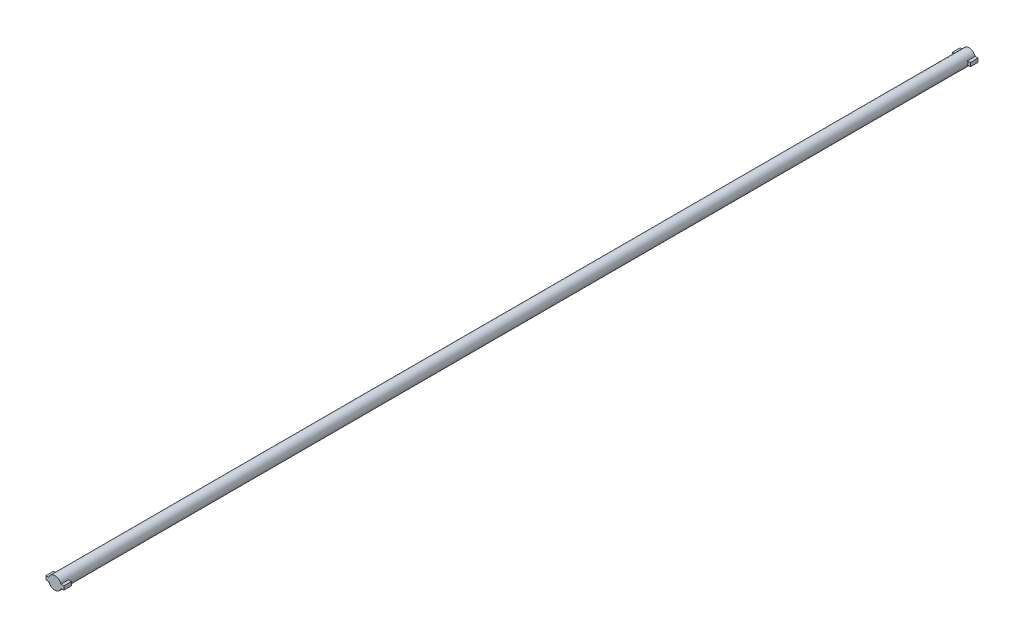
SolidWorks part; units mm, degrees
material "AISI 1020 Steel, Cold Rolled"
ref_plane "Front Plane" through (0, 0, 0) normal (0, 0, 1) x (1, 0, 0)
ref_plane "Top Plane" through (0, 0, 0) normal (0, 1, 0) x (1, 0, 0)
ref_plane "Right Plane" through (0, 0, 0) normal (1, 0, 0) x (0, 0, -1)
sketch "Sketch1" plane through (0, 0, 0) normal (0, 0, 1) x (1, 0, 0)
  circle A0 centre (0, 0) radius 3.175
  dimension "D1" = 6.35
extrude "Boss-Extrude1" add sketch "Sketch1" along normal blind 457.2
sketch "Sketch3" plane through (0, 0, 457.2) normal (0, 0, 1) x (1, 0, 0)
  line L0 (3.175, 0) -> (4.445, 0) construction
  line L1 (4.445, 0.9525) -> (4.445, -0.9525)
  line L2 (4.445, 0.9525) -> (3.0288, 0.9525)
  line L3 (4.445, -0.9525) -> (3.0288, -0.9525)
  circle A0 centre (0, 0) radius 3.175 construction
  arc A1 (3.0288, -0.9525) -> (3.0288, 0.9525) centre (0, 0) ccw
  dimension "D1" = 1.905
  dimension "D2" = 1.27
extrude "Boss-Extrude2" add sketch "Sketch3" against normal blind 3.81
pattern_circular "CirPattern1" count 2 over 360 about axis through (0, 0, 0) along (0, 0, 1) of "Boss-Extrude2"
pattern_linear "LPattern1" count 2 spacing 453.39 along (0, 0, -1) of "CirPattern1", "Boss-Extrude2"
ref_plane "Plane2" through (3.175, 0, 0) normal (1, 0, 0) x (0, 0, -1)
ref_plane "Plane3" through (-3.175, 0, 0) normal (1, 0, 0) x (0, 0, -1)
